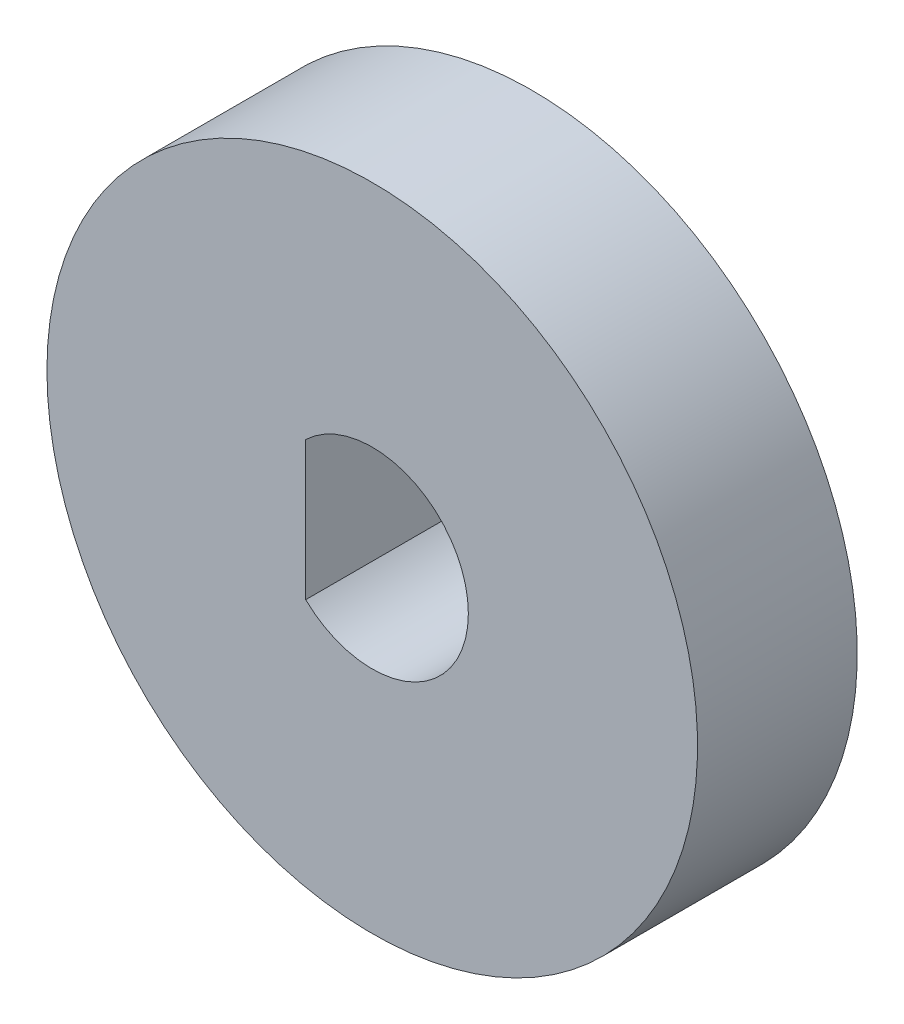
SolidWorks part; units mm, degrees
ref_plane "Front Plane" through (0, 0, 0) normal (0, 0, 1) x (1, 0, 0)
ref_plane "Top Plane" through (0, 0, 0) normal (0, 1, 0) x (1, 0, 0)
ref_plane "Right Plane" through (0, 0, 0) normal (1, 0, 0) x (0, 0, -1)
sketch "Sketch2" plane through (0, 0, 0) normal (0, 0, 1) x (1, 0, 0)
  circle A0 centre (0, 0) radius 11
  dimension "D1" = 22
extrude "Boss-Extrude1" add sketch "Sketch2" along normal blind 5.4
sketch "Sketch3" plane through (0, 0, 0) normal (0, 0, -1) x (-1, 0, 0)
  line L1 (2.25, 2.3452) -> (3.25, 2.3452) construction
  line L2 (2.25, 2.3452) -> (2.25, -2.3452)
  line L3 (2.25, -2.3452) -> (3.25, -2.3452) construction
  line L4 (3.25, 2.3452) -> (3.25, -2.3452) construction
  circle A0 centre (0, 0) radius 3.25 construction
  arc A1 (2.25, -2.3452) -> (2.25, 2.3452) centre (0, 0) cw
  dimension "D1" = 6.5
  dimension "D2" = 1
extrude "Cut-Extrude4" cut sketch "Sketch3" against normal through all contours A1 L2
equation "\"D1@Sketch2\"=21.5mm+.5mm"
